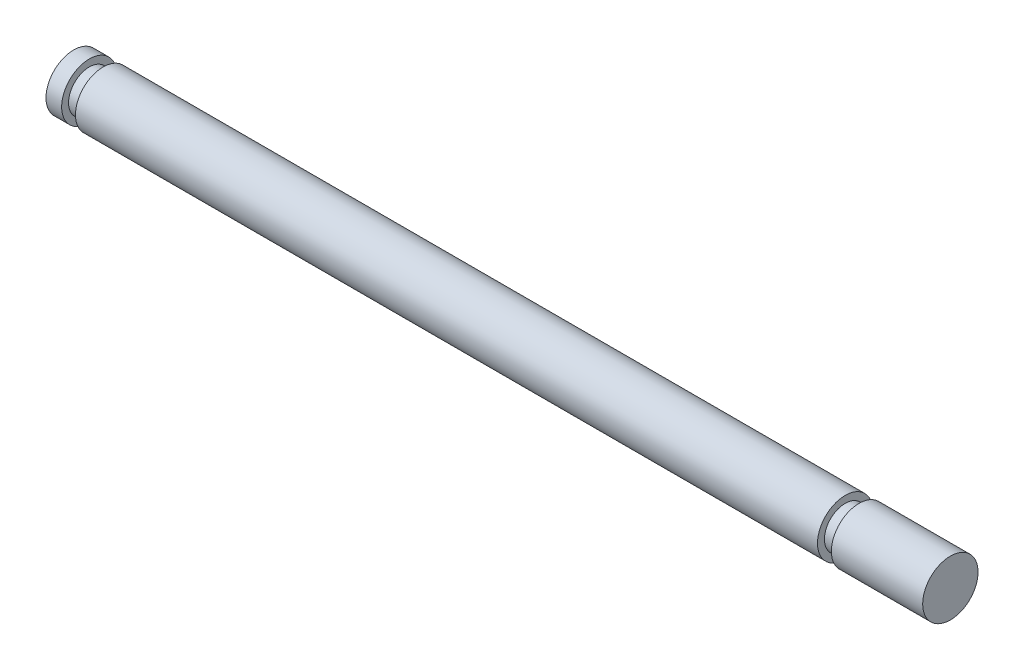
SolidWorks part; units mm, degrees
ref_plane "Front Plane" through (0, 0, 0) normal (0, 0, 1) x (1, 0, 0)
ref_plane "Top Plane" through (0, 0, 0) normal (0, 1, 0) x (1, 0, 0)
ref_plane "Right Plane" through (0, 0, 0) normal (1, 0, 0) x (0, 0, -1)
sketch "Sketch1" plane through (0, 0, 0) normal (0, 0, 1) x (1, 0, 0)
  line L0 (0, 0) -> (0, 50)
  line L1 (0, 50) -> (28.2, 50)
  line L2 (28.2, 50) -> (28.2, 37.5)
  line L3 (28.2, 37.5) -> (53.2, 37.5)
  line L4 (53.2, 37.5) -> (53.2, 50)
  line L5 (0, 0) -> (1583, 0)
  line L6 (1583, 0) -> (1583, 50)
  line L7 (1583, 50) -> (1418.1, 50)
  line L8 (1418.1, 50) -> (1418.1, 37.5)
  line L9 (1418.1, 37.5) -> (1393.1, 37.5)
  line L10 (1393.1, 37.5) -> (1393.1, 50)
  line L11 (1393.1, 50) -> (53.2, 50)
  dimension "D1" = 50
  dimension "D2" = 28.2
  dimension "D3" = 12.5
  dimension "D4" = 12.5
  dimension "D5" = 25
  dimension "D6" = 1583
  dimension "D7" = 164.9
  dimension "D8" = 12.5
  dimension "D9" = 25
revolve "Revolve1" add sketch "Sketch1" angle 360 about L5
